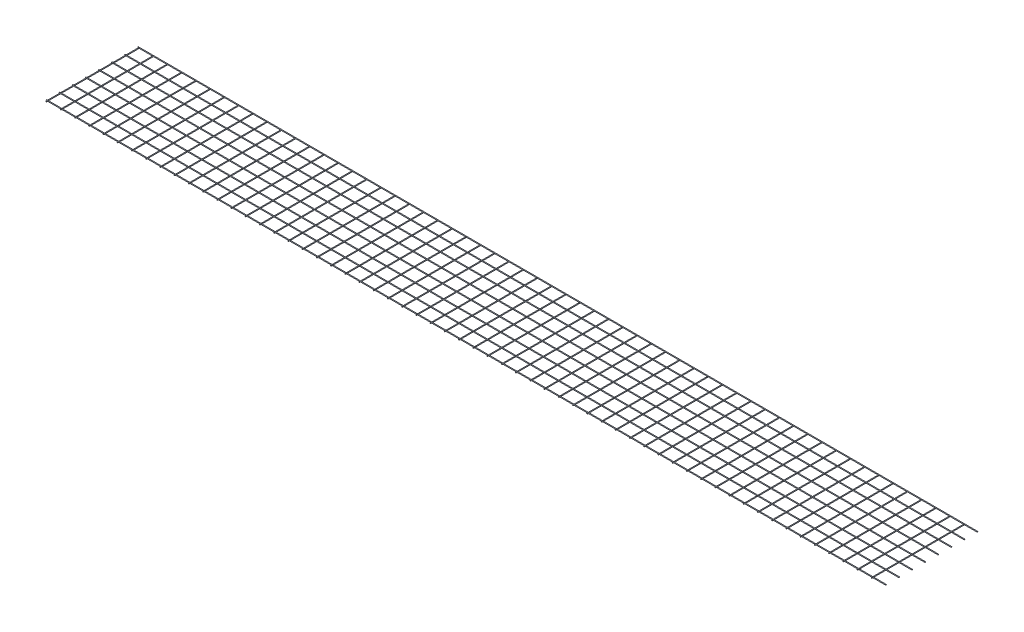
SolidWorks part; units mm, degrees
ref_plane "Front Plane" through (0, 0, 0) normal (0, 0, 1) x (1, 0, 0)
ref_plane "Top Plane" through (0, 0, 0) normal (0, 1, 0) x (1, 0, 0)
ref_plane "Right Plane" through (0, 0, 0) normal (1, 0, 0) x (0, 0, -1)
sketch "Sketch1" plane through (0, 0, 0) normal (0, 0, 1) x (1, 0, 0)
  line L0 (55, 0) -> (-55, 0) construction
  circle A0 centre (-80.0795, 0) radius 2.5
  circle A1 centre (19.9205, 0) radius 2.5
  circle A2 centre (119.9205, 0) radius 2.5
  circle A3 centre (219.9205, 0) radius 2.5
  circle A4 centre (319.9205, 0) radius 2.5
  circle A5 centre (419.9205, 0) radius 2.5
  circle A6 centre (519.9205, 0) radius 2.5
  circle A7 centre (619.9205, 0) radius 2.5
  circle A8 centre (719.9205, 0) radius 2.5
  circle A9 centre (819.9205, 0) radius 2.5
  circle A10 centre (919.9205, 0) radius 2.5
  circle A11 centre (1019.9205, 0) radius 2.5
  circle A12 centre (1119.9205, 0) radius 2.5
  circle A13 centre (1219.9205, 0) radius 2.5
  circle A14 centre (1319.9205, 0) radius 2.5
  circle A15 centre (1419.9205, 0) radius 2.5
  circle A16 centre (1519.9205, 0) radius 2.5
  circle A17 centre (1619.9205, 0) radius 2.5
  circle A18 centre (1719.9205, 0) radius 2.5
  circle A19 centre (1819.9205, 0) radius 2.5
  circle A20 centre (1919.9205, 0) radius 2.5
  circle A21 centre (2019.9205, 0) radius 2.5
  circle A22 centre (2119.9205, 0) radius 2.5
  circle A23 centre (2219.9205, 0) radius 2.5
  circle A24 centre (2319.9205, 0) radius 2.5
  circle A25 centre (2419.9205, 0) radius 2.5
  circle A26 centre (2519.9205, 0) radius 2.5
  circle A27 centre (2619.9205, 0) radius 2.5
  circle A28 centre (2719.9205, 0) radius 2.5
  circle A29 centre (2819.9205, 0) radius 2.5
  circle A30 centre (2919.9205, 0) radius 2.5
  circle A31 centre (3019.9205, 0) radius 2.5
  circle A32 centre (3119.9205, 0) radius 2.5
  circle A33 centre (3219.9205, 0) radius 2.5
  circle A34 centre (3319.9205, 0) radius 2.5
  circle A35 centre (3419.9205, 0) radius 2.5
  circle A36 centre (3519.9205, 0) radius 2.5
  circle A37 centre (3619.9205, 0) radius 2.5
  circle A38 centre (3719.9205, 0) radius 2.5
  circle A39 centre (3819.9205, 0) radius 2.5
  circle A40 centre (3919.9205, 0) radius 2.5
  circle A41 centre (4019.9205, 0) radius 2.5
  circle A42 centre (4119.9205, 0) radius 2.5
  circle A43 centre (4219.9205, 0) radius 2.5
  circle A44 centre (4319.9205, 0) radius 2.5
  circle A45 centre (4419.9205, 0) radius 2.5
  circle A46 centre (4519.9205, 0) radius 2.5
  circle A47 centre (4619.9205, 0) radius 2.5
  circle A48 centre (4719.9205, 0) radius 2.5
  circle A49 centre (4819.9205, 0) radius 2.5
  circle A50 centre (4919.9205, 0) radius 2.5
  circle A51 centre (5019.9205, 0) radius 2.5
  circle A52 centre (5119.9205, 0) radius 2.5
  circle A53 centre (5219.9205, 0) radius 2.5
  circle A54 centre (5319.9205, 0) radius 2.5
  circle A55 centre (5419.9205, 0) radius 2.5
  circle A56 centre (5519.9205, 0) radius 2.5
  circle A57 centre (5619.9205, 0) radius 2.5
  circle A58 centre (5719.9205, 0) radius 2.5
  dimension "D1" = 59
extrude "Boss-Extrude1" add sketch "Sketch1" along normal blind 650
ref_plane "Plane1" through (-82.5795, 0, 0) normal (-1, 0, 0) x (0, 0, 1)
sketch "Sketch2" plane through (-82.5795, 0, 0) normal (-1, 0, 0) x (0, 0, 1)
  circle A0 centre (2.5, 5) radius 2.5
  circle A1 centre (94.5, 5) radius 2.5
  circle A2 centre (186.5, 5) radius 2.5
  circle A3 centre (278.5, 5) radius 2.5
  circle A4 centre (370.5, 5) radius 2.5
  circle A5 centre (462.5, 5) radius 2.5
  circle A6 centre (554.5, 5) radius 2.5
  circle A7 centre (646.5, 5) radius 2.5
  dimension "D1" = 8
extrude "Boss-Extrude2" add sketch "Sketch2" against normal blind 5900 separate body
